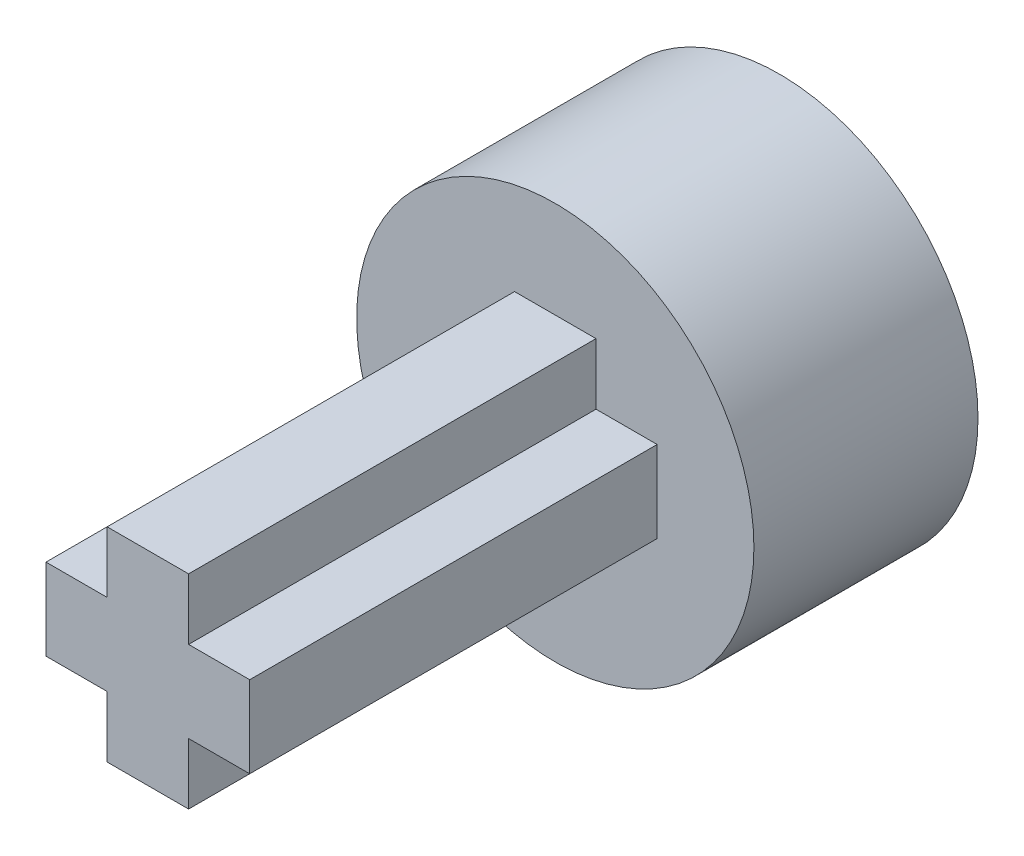
SolidWorks part; units mm, degrees
ref_plane "Front Plane" through (0, 0, 0) normal (0, 0, 1) x (1, 0, 0)
ref_plane "Top Plane" through (0, 0, 0) normal (0, 1, 0) x (1, 0, 0)
ref_plane "Right Plane" through (0, 0, 0) normal (1, 0, 0) x (0, 0, -1)
sketch "Sketch1" plane through (0, 0, 0) normal (0, 0, 1) x (1, 0, 0)
  circle A0 centre (0, 0) radius 2.875
  circle A1 centre (0, 0) radius 4.875
  dimension "D1" = 5.75
  dimension "D2" = 2
extrude "Boss-Extrude1" add sketch "Sketch1" along normal blind 3.5
sketch "Sketch2" plane through (0, 0, 3.5) normal (0, 0, 1) x (1, 0, 0)
  circle A0 centre (0, 0) radius 4.875
  circle A1 centre (0, 0) radius 4.875 construction
extrude "Boss-Extrude2" add sketch "Sketch2" along normal blind 2
chamfer "Chamfer1" distance 0.5 angle 45 1 edges at (2.875, 0, 0)
sketch "Sketch3" plane through (0, 0, 5.5) normal (0, 0, 1) x (1, 0, 0)
  line L0 (0, 0) -> (1, 2.5) construction
  line L1 (-1, 2.5) -> (1, 2.5)
  line L2 (-1, 2.5) -> (-1, 1)
  line L3 (-1, -2.5) -> (1, -2.5)
  line L4 (1, 2.5) -> (1, 1)
  line L5 (2.5, -1) -> (1, -1)
  line L6 (2.5, -1) -> (2.5, 1)
  line L7 (2.5, 1) -> (1, 1)
  line L8 (-2.5, -1) -> (-2.5, 1)
  line L9 (0, 0) -> (-2.5, -1) construction
  line L10 (-1, -2.5) -> (0, 0) construction
  line L11 (0, 0) -> (2.5, 1) construction
  line L12 (-1, 1) -> (-2.5, 1)
  line L13 (-1, -1) -> (-1, -2.5)
  line L14 (-1, -1) -> (-2.5, -1)
  line L15 (1, -1) -> (1, -2.5)
  point P9 (2.2085, -0.6171)
  dimension "D1" = 2
  dimension "D2" = 5
extrude "Boss-Extrude3" add sketch "Sketch3" along normal blind 10
